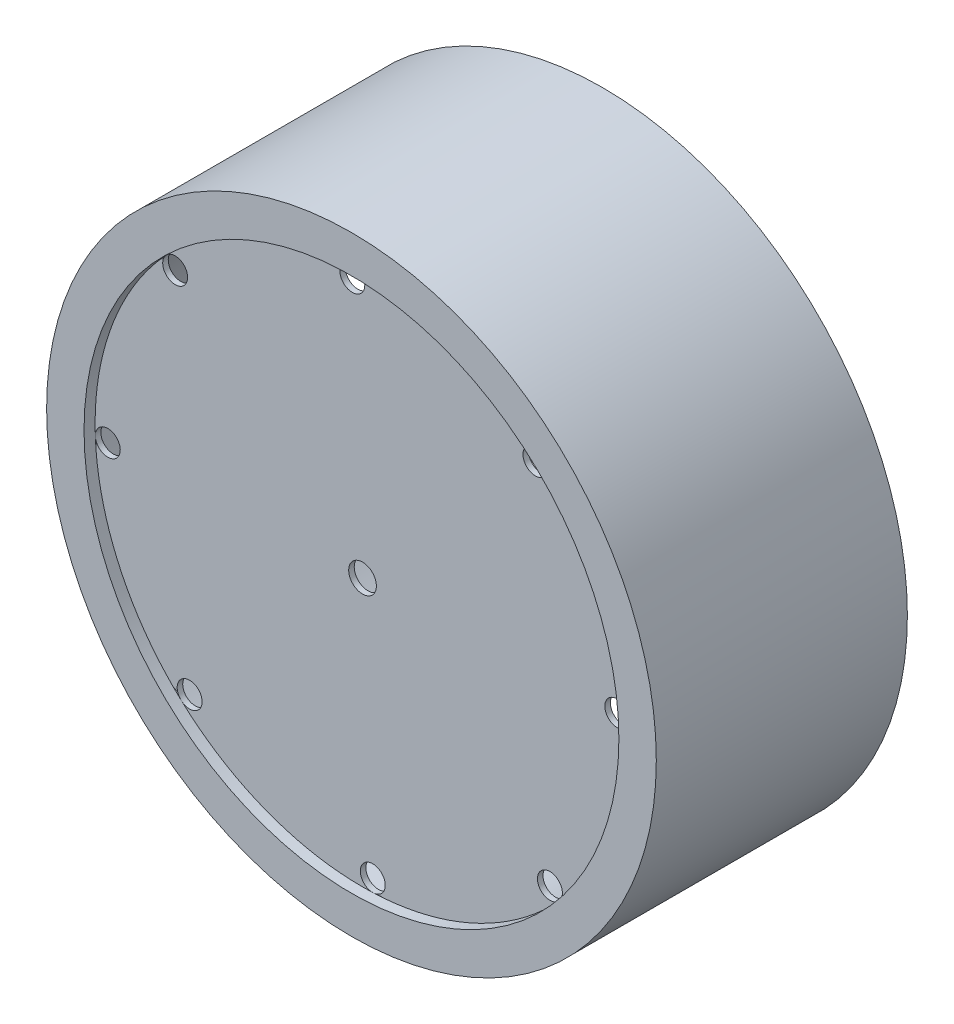
SolidWorks part; units mm, degrees
ref_plane "前视基准面" through (0, 0, 0) normal (0, 0, 1) x (1, 0, 0)
ref_plane "上视基准面" through (0, 0, 0) normal (0, 1, 0) x (1, 0, 0)
ref_plane "右视基准面" through (0, 0, 0) normal (1, 0, 0) x (0, 0, -1)
sketch "草图1" plane through (0, 0, 0) normal (0, 0, 1) x (1, 0, 0)
  circle A0 centre (0, 0) radius 55
extrude "凸台-拉伸3" add sketch "草图1" along normal blind 45.3
sketch "草图5" plane through (0, 0, 0) normal (0, 0, -1) x (-1, 0, 0)
  circle A0 centre (0, 0) radius 50
extrude "切除-拉伸3" cut sketch "草图5" against normal blind 42.3
sketch "草图6" plane through (0, 0, 42.3) normal (0, 0, -1) x (-1, 0, 0)
  circle A1 centre (31.1942, -33.8071) radius 2.25
  circle A2 centre (-1.8476, -45.9629) radius 2.25
  circle A3 centre (-33.8071, -31.1942) radius 2.25
  circle A4 centre (-45.9629, 1.8476) radius 2.25
  circle A5 centre (-31.1942, 33.8071) radius 2.25
  circle A6 centre (1.8476, 45.9629) radius 2.25
  circle A7 centre (33.8071, 31.1942) radius 2.25
  circle A8 centre (45.9629, -1.8476) radius 2.25
  point P22 (0, 0)
  dimension "D1" = 8
sketch "草图8" plane through (0, 0, 45.3) normal (0, 0, 1) x (1, 0, 0)
  circle A0 centre (0, 0) radius 48.25
extrude "切除-拉伸4" cut sketch "草图8" against normal blind 2
extrude "切除-拉伸6" cut sketch "草图6" against normal blind 2 contours A2 | A3 | A4 | A5 | A1 | A6 | A7 | A8
sketch "草图9" plane through (0, 0, 0) normal (0, 0, -1) x (-1, 0, 0)
  line L0 (0, 0) -> (55, 0)
  circle A0 centre (0, 0) radius 55 construction
sketch "草图10" plane through (0, 0, 42.3) normal (0, 0, -1) x (-1, 0, 0)
  circle A0 centre (0, 0) radius 2.5
extrude "切除-拉伸7" cut sketch "草图10" against normal blind 5
